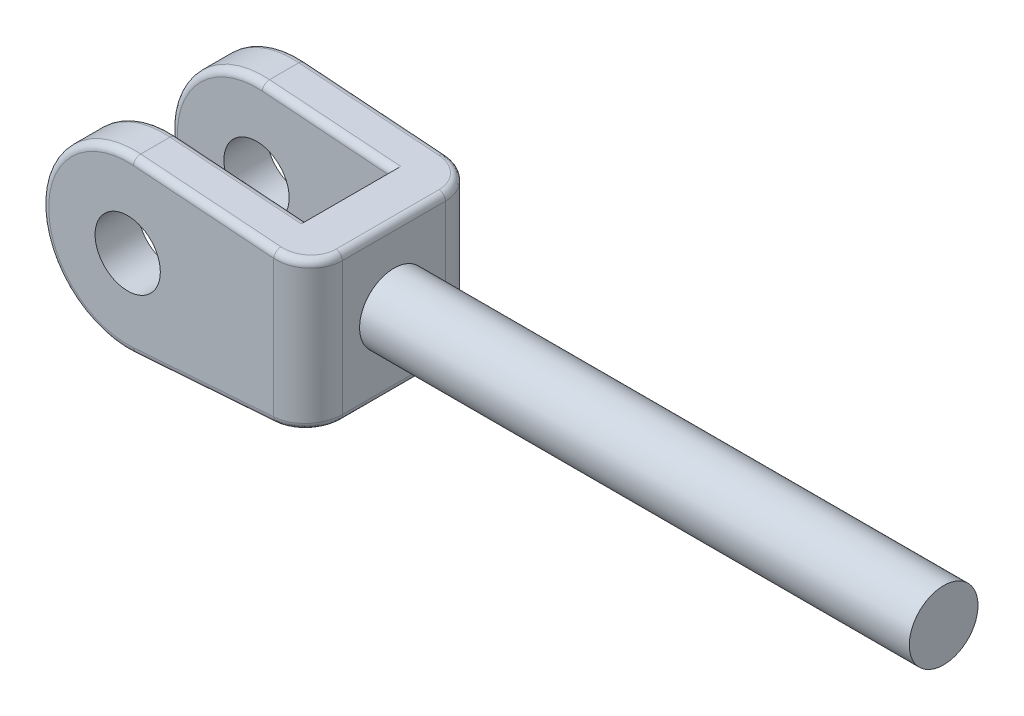
SolidWorks part; units mm, degrees
ref_plane "Front Plane" through (0, 0, 0) normal (0, 0, 1) x (1, 0, 0)
ref_plane "Top Plane" through (0, 0, 0) normal (0, 1, 0) x (1, 0, 0)
ref_plane "Right Plane" through (0, 0, 0) normal (1, 0, 0) x (0, 0, -1)
sketch "Sketch2" plane through (0, 0, 0) normal (1, 0, 0) x (0, 0, -1)
  circle A0 centre (0, 0) radius 1
  dimension "D1" = 2
extrude "Boss-Extrude1" add sketch "Sketch2" along normal blind 16
sketch "Sketch3" plane through (0, 0, 0) normal (0, 0, 1) x (1, 0, 0)
  line L0 (0, 0) -> (-7.75, 0) construction
  line L1 (0, -2.125) -> (0, 2.125)
  line L2 (0, 2.125) -> (-5.0688, 2.4934)
  line L3 (0, -2.125) -> (-5.0688, -2.4934)
  circle A0 centre (-5.25, 0) radius 0.95
  arc A1 (-5.0688, 2.4934) -> (-5.0688, -2.4934) centre (-5.25, 0) ccw
  dimension "D2" = 5
  dimension "D3" = 1.9
  dimension "D1" = 7.75
  dimension "D4" = 2.5
  dimension "D5" = 4.25
extrude "Boss-Extrude2" add sketch "Sketch3" along normal mid plane 5
sketch "Sketch4" plane through (0, 0, 0) normal (0, 1, 0) x (1, 0, 0)
  line L0 (0, 0) -> (-7.75, 0) construction
  line L1 (-7.75, 2.5) -> (-7.75, -2.5) construction
  line L2 (-5.0688, -2.5) -> (-5.0688, 2.5) construction
  line L6 (-1.25, 1.25) -> (-1.25, -1.25)
  line L7 (-5.0688, 0) -> (-1.25, -1.25) construction
  line L8 (-5.0688, 0) -> (-1.25, 1.25) construction
  line L10 (0, -2.5) -> (0, 2.5) construction
  line L11 (-1.25, 1.25) -> (-7.75, 1.25)
  line L12 (-7.75, 1.25) -> (-7.75, -1.25)
  line L13 (-7.75, -1.25) -> (-1.25, -1.25)
  line L14 (0, 2.5) -> (-5.0688, 2.5) construction
  point P3 (-5.0688, 0)
  dimension "D1" = 1.25
  dimension "D2" = 1.25
extrude "Cut-Extrude1" cut sketch "Sketch4" against normal through all both and the other way through all
fillet "Fillet1" radius 1 2 edges at (0, 0, -2.5) (0, 0, 2.5)
fillet "Fillet2" radius 0.2 12 edges at (-0.2929, 2.1463, 2.2071) (0, 2.125, 0) (-0.2929, 2.1463, -2.2071) (-3.0344, 2.3456, -2.5) (-7.75, 0, -2.5) (-3.0344, -2.3456, -2.5) (-0.2929, -2.1463, -2.2071) (0, -2.125, 0) (-0.2929, -2.1463, 2.2071) (-3.0344, -2.3456, 2.5) (-7.75, 0, 2.5) (-3.0344, 2.3456, 2.5)
fillet "Fillet3" radius 0.2 3 edges at (-3.1594, -2.3546, -1.25) (-7.75, 0, -1.25) (-3.1594, 2.3546, -1.25)
fillet "Fillet4" radius 0.2 3 edges at (-3.1594, -2.3546, 1.25) (-7.75, 0, 1.25) (-3.1594, 2.3546, 1.25)
